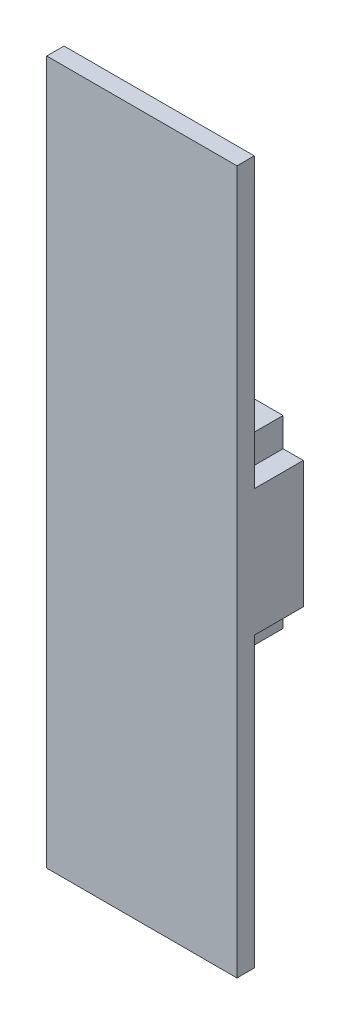
SolidWorks part; units mm, degrees
ref_plane "Ön Düzlem" through (0, 0, 0) normal (0, 0, 1) x (1, 0, 0)
ref_plane "Üst Düzlem" through (0, 0, 0) normal (0, 1, 0) x (1, 0, 0)
ref_plane "Sağ Düzlem" through (0, 0, 0) normal (1, 0, 0) x (0, 0, -1)
sketch "Sketch1" plane through (0, 0, 0) normal (0, 0, 1) x (1, 0, 0)
  line L0 (-16.5, 11) -> (16.5, 11)
  line L1 (-11.5, 6) -> (0, 6) construction
  line L2 (-11.5, 0) -> (-11.5, -6) construction
  line L3 (-11.5, -6) -> (11.5, -6) construction
  line L4 (11.5, 6) -> (11.5, -6) construction
  line L5 (0, 0) -> (11.5, -6) construction
  line L6 (-11.5, -6) -> (0, 0) construction
  line L7 (16.5, 11) -> (16.5, -11)
  line L8 (-16.5, -11) -> (16.5, -11)
  line L9 (-16.5, 11) -> (-16.5, -11)
  line L10 (0, 0) -> (0, 6) construction
  line L11 (-13, 16) -> (-5, 16)
  line L12 (-13, 16) -> (-13, 11)
  line L13 (-13, 11) -> (-5, 11)
  line L14 (-5, 16) -> (-5, 11)
  line L15 (5, 16) -> (5, 11)
  line L16 (13, 16) -> (13, 11)
  line L17 (13, 16) -> (5, 16)
  line L18 (0, 0) -> (-11.5, 0) construction
  line L19 (13, -16) -> (13, -11)
  line L20 (13, -16) -> (5, -16)
  line L21 (5, -16) -> (5, -11)
  line L22 (-5, -16) -> (-5, -11)
  line L23 (-13, -16) -> (-13, -11)
  line L24 (-13, -16) -> (-5, -16)
  line L25 (0, 0) -> (11.5, 6) construction
  line L26 (0, 6) -> (11.5, 6) construction
  line L27 (-11.5, 6) -> (11.5, 6) construction
  line L28 (-11.5, 6) -> (0, 0) construction
  line L29 (-11.5, 6) -> (-11.5, 0) construction
  line L30 (-11.5, 6) -> (-11.5, -6) construction
  circle A0 centre (-14, 0) radius 1 construction
  circle A1 centre (14, 0) radius 1 construction
  point P0 (0, 0)
  dimension "D7" = 2
  dimension "D1" = 12
  dimension "D2" = 23
  dimension "D4" = 3.5
  dimension "D5" = 5
  dimension "D6" = 8
  dimension "D8" = 2.5
  dimension "D3" = 5
extrude "Boss-Extrude1" add sketch "Sketch1" along normal mid plane 5 contours L0 L9 L8 L7 L1 L4 L3 L2 A0 A1 | L23 L24 L22 L8 | L21 L20 L19 L8 | L16 L17 L15 L0 | L14 L11 L12 L0
sketch "草图1" plane through (0, 0, 2.5) normal (0, 0, 1) x (1, 0, 0)
  line L1 (-16.5, 11) -> (16.5, 11)
  line L2 (-16.5, 11) -> (-16.5, -11)
  line L3 (-16.5, -11) -> (16.5, -11)
  line L4 (16.5, 11) -> (16.5, -11)
extrude "凸台-拉伸1" add sketch "草图1" along normal blind 6.5
sketch "草图2" plane through (0, 11, 0) normal (0, 1, 0) x (1, 0, 0)
  line L0 (16.5, -9) -> (16.5, 2.5) construction
  line L1 (-16.5, -9) -> (16.5, -9)
  line L2 (-16.5, -9) -> (-16.5, -6)
  line L3 (-16.5, -6) -> (16.5, -6)
  line L4 (16.5, -9) -> (16.5, -6)
  line L5 (13, -2.5) -> (5, -2.5) construction
  dimension "D1" = 3.5
extrude "凸台-拉伸2" add sketch "草图2" along normal blind 50
mirror "镜向1" about plane through (0, 0, 0) normal (0, 1, 0) of "凸台-拉伸2"
